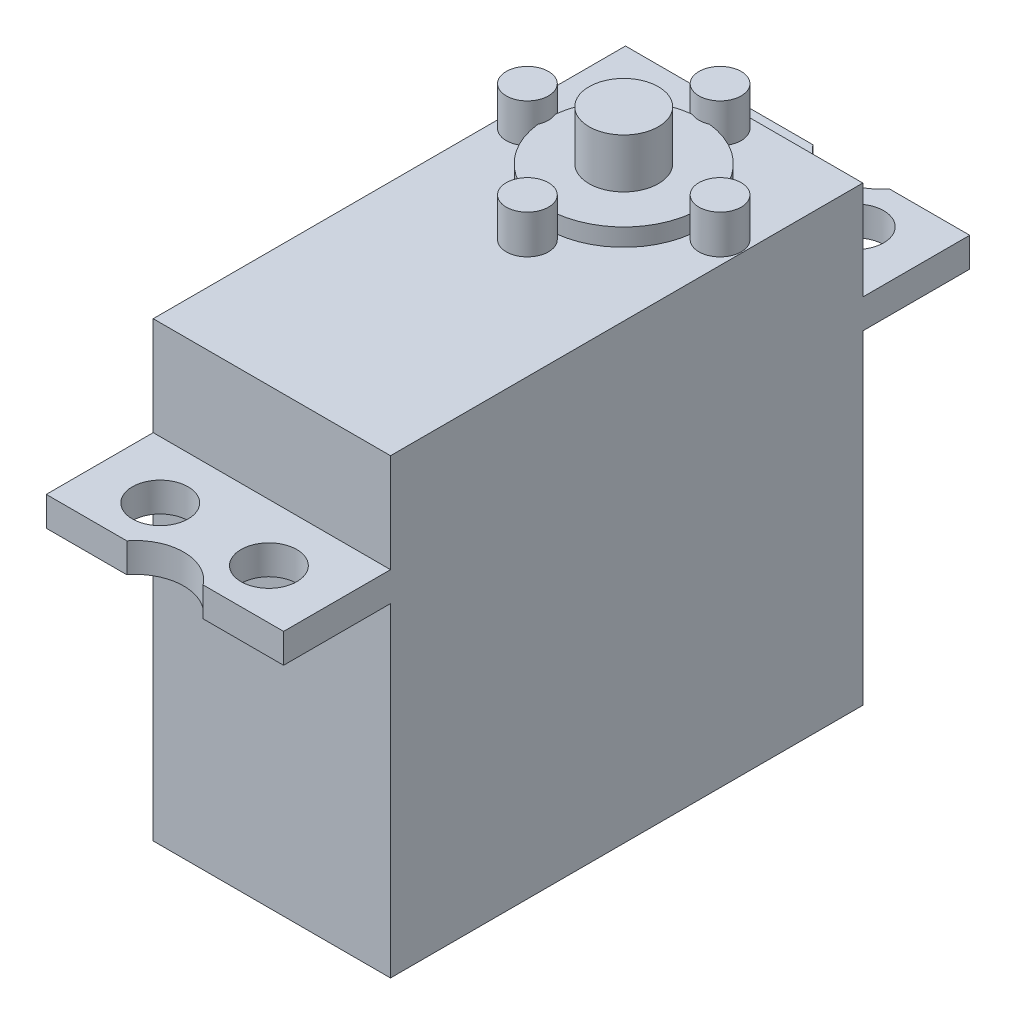
SolidWorks part; units mm, degrees
ref_plane "Plan de face" through (0, 0, 0) normal (0, 0, 1) x (1, 0, 0)
ref_plane "Plan de dessus" through (0, 0, 0) normal (0, 1, 0) x (1, 0, 0)
ref_plane "Plan de droite" through (0, 0, 0) normal (1, 0, 0) x (0, 0, -1)
sketch "Esquisse1" plane through (0, 0, 0) normal (1, 0, 0) x (0, 0, -1)
  line L0 (0, 0) -> (40.2, 0)
  line L1 (40.2, 0) -> (40.2, 27.6)
  line L2 (40.2, 27.6) -> (49.3, 27.6)
  line L3 (49.3, 27.6) -> (49.3, 30.1)
  line L4 (49.3, 30.1) -> (40.2, 30.1)
  line L5 (40.2, 30.1) -> (40.2, 38.5)
  line L6 (40.2, 38.5) -> (0, 38.5)
  line L7 (0, 38.5) -> (0, 30.1)
  line L8 (0, 30.1) -> (-9.1, 30.1)
  line L9 (-9.1, 30.1) -> (-9.1, 27.6)
  line L10 (-9.1, 27.6) -> (0, 27.6)
  line L11 (0, 27.6) -> (0, 0)
  dimension "D1" = 38.5
  dimension "D2" = 2.5
  dimension "D3" = 40.2
  dimension "D4" = 27.6
  dimension "D5" = 9.1
extrude "Boss.-Extru.1" add sketch "Esquisse1" along normal blind 20.2
sketch "Esquisse2" plane through (0, 30.1, 0) normal (0, 1, 0) x (1, 0, 0)
  line L0 (10.1, 40.2) -> (10.1, 49.3) construction
  line L1 (20.2, 40.2) -> (0, 40.2) construction
  line L2 (20.2, 49.3) -> (0, 49.3) construction
  line L3 (20.2, 40.2) -> (0, 40.2) construction
  line L4 (0, 20.1) -> (20.2, 20.1) construction
  line L5 (0, 40.2) -> (0, 0) construction
  line L6 (20.2, 40.2) -> (20.2, 0) construction
  circle A0 centre (10.1, 51.8008) radius 4.1008
  circle A1 centre (5.475, 45.075) radius 2.375
  circle A2 centre (14.725, 45.075) radius 2.375
  circle A3 centre (14.725, -4.875) radius 2.375
  circle A4 centre (5.475, -4.875) radius 2.375
  circle A5 centre (10.1, -11.6008) radius 4.1008
  point P24 (10.1, 47.7)
  point P25 (6.85, 49.3)
  point P26 (13.35, 49.3)
  dimension "D1" = 9.25
  dimension "D2" = 4.75
  dimension "D6" = 8.2016
  dimension "D3" = 4.875
  dimension "D4" = 7.5
  dimension "D5" = 6.5
extrude "Enlèv. mat.-Extru.1" cut sketch "Esquisse2" against normal through all
sketch "Esquisse3" plane through (0, 38.5, 0) normal (0, 1, 0) x (1, 0, 0)
  line L0 (10.1, 40.2) -> (10.1, 0) construction
  line L1 (20.2, 40.2) -> (0, 40.2) construction
  line L2 (20.2, 0) -> (0, 0) construction
  line L3 (20.2, 40.2) -> (0, 40.2) construction
  circle A0 centre (10.1, 29.95) radius 2.95
  dimension "D1" = 5.9
  dimension "D2" = 10.25
extrude "Boss.-Extru.2" add sketch "Esquisse3" along normal blind 5.7
sketch "Esquisse4" plane through (0, 38.5, 0) normal (0, 1, 0) x (1, 0, 0)
  line L0 (10.1, 29.95) -> (0, 29.95) construction
  line L1 (0, 40.2) -> (0, 0) construction
  line L2 (10.1, 29.95) -> (1.9, 29.95) construction
  line L3 (10.1, 29.95) -> (10.1, 38.15) construction
  circle A0 centre (1.9, 29.95) radius 1.8
  circle A1 centre (10.1, 38.15) radius 1.8
  circle A2 centre (18.3, 29.95) radius 1.8
  circle A3 centre (10.1, 21.75) radius 1.8
  dimension "D3" = 3.6
  dimension "D2" = 90
  dimension "D4" = 8.2
  dimension "D1" = 4
extrude "Boss.-Extru.3" add sketch "Esquisse4" along normal blind 3.3
sketch "Esquisse5" plane through (0, 38.5, 0) normal (0, 1, 0) x (1, 0, 0)
  circle A0 centre (10.1, 29.95) radius 6.6
  dimension "D1" = 13.2
extrude "Boss.-Extru.4" add sketch "Esquisse5" along normal blind 1.5
sketch "Esquisse6" plane through (0, 0, -40.2) normal (0, 0, -1) x (-1, 0, 0)
  line L0 (-10.1, 0) -> (-10.1, 27.6) construction
  line L1 (-20.2, 0) -> (0, 0) construction
  line L2 (-13.35, 27.6) -> (-6.85, 27.6) construction
  line L3 (-13.85, 2.5) -> (-13.85, 7.5)
  line L4 (-6.35, 2.5) -> (-6.35, 7.5)
  line L5 (-13.85, 7.5) -> (-6.35, 7.5)
  line L6 (-6.35, 2.5) -> (-13.85, 2.5)
  dimension "D1" = 7.5
  dimension "D2" = 5
  dimension "D3" = 2.5
extrude "Boss.-Extru.5" add sketch "Esquisse6" along normal blind 1
sketch "Esquisse7" plane through (0, 0, -41.2) normal (0, 0, -1) x (-1, 0, 0)
  line L0 (-10.1, 7.5) -> (-10.1, 2.5) construction
  line L1 (-6.35, 7.5) -> (-13.85, 7.5) construction
  line L2 (-13.85, 2.5) -> (-6.35, 2.5) construction
  line L3 (-11.5, 5) -> (-8.7, 5) construction
  line L4 (-11.5, 6.5) -> (-8.7, 6.5)
  line L5 (-11.5, 3.5) -> (-8.7, 3.5)
  arc A0 (-11.5, 6.5) -> (-11.5, 3.5) centre (-11.5, 5) ccw
  arc A1 (-8.7, 3.5) -> (-8.7, 6.5) centre (-8.7, 5) ccw
  point P8 (-10.1, 5)
  dimension "D1" = 3
  dimension "D2" = 2.8
extrude "Boss.-Extru.6" add sketch "Esquisse7" along normal blind 4
